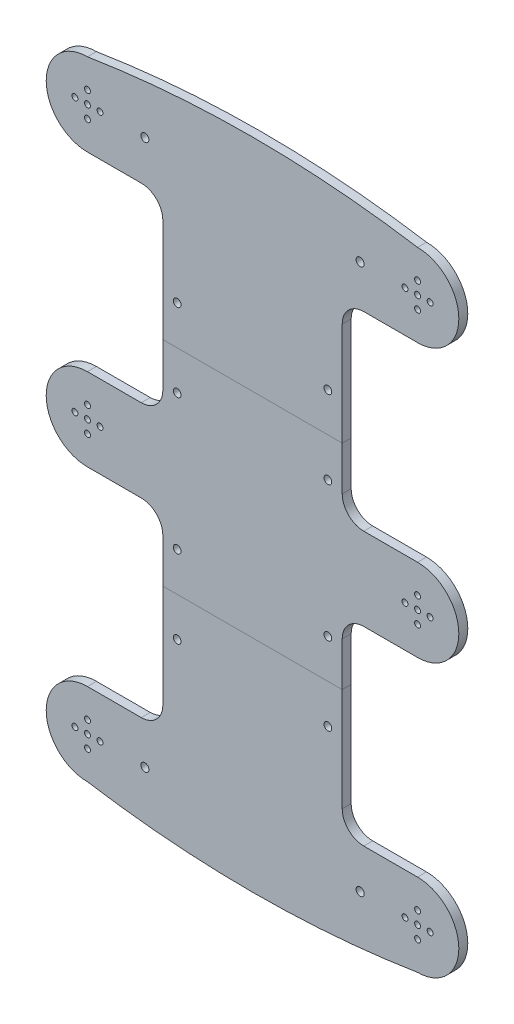
SolidWorks part; units mm, degrees
ref_plane "Płaszczyzna przednia" through (0, 0, 0) normal (0, 0, 1) x (1, 0, 0)
ref_plane "Płaszczyzna górna" through (0, 0, 0) normal (0, 1, 0) x (1, 0, 0)
ref_plane "Płaszczyzna prawa" through (0, 0, 0) normal (1, 0, 0) x (0, 0, -1)
sketch "Szkic1" plane through (0, 0, 0) normal (0, 0, 1) x (1, 0, 0)
  line L0 (-203.4983, 203.4983) -> (200.3017, -200.3017) construction
  line L5 (-225.8431, 0) -> (204.6382, 0) construction
  line L6 (0, 259.0582) -> (0, -261.5805) construction
  line L7 (202.2417, 202.2417) -> (-202.2417, -202.2417) construction
  line L9 (-95, 116) -> (-57, 116) construction
  line L10 (-95, 116) -> (-95, 36) construction
  line L11 (-95, 36) -> (-57, 36) construction
  line L12 (-57, 116) -> (-57, 36) construction
  line L28 (-50, -116.999) -> (-50, -35.001)
  line L29 (50, -116.999) -> (50, -35.001)
  line L31 (-95, 116) -> (-57, 36) construction
  line L32 (-57, 116) -> (-95, 36) construction
  line L33 (-62, -23.001) -> (-92, -23.001)
  line L38 (-50, 35.001) -> (-50, 116.999)
  line L39 (-62, 23.001) -> (-92, 23.001)
  line L42 (50, 35.001) -> (50, 116.999)
  line L43 (-112.0619, 76) -> (134.9818, 76) construction
  line L44 (-112.0619, -76) -> (134.9818, -76) construction
  line L46 (-62, 128.999) -> (-92, 128.999)
  line L48 (-62, -128.999) -> (-92, -128.999)
  line L53 (62, -128.999) -> (92, -128.999)
  line L54 (62, 23.001) -> (92, 23.001)
  line L55 (62, -23.001) -> (92, -23.001)
  line L57 (62, 128.999) -> (92, 128.999)
  circle A0 centre (-92, 7.001) radius 1.65
  circle A4 centre (-92, 0) radius 7.001 construction
  circle A5 centre (-84.999, 0) radius 1.65
  circle A6 centre (-92, -7.001) radius 1.65
  circle A7 centre (-99.001, 0) radius 1.65
  arc A19 (-92, 23.001) -> (-92, -23.001) centre (-92, 0) ccw
  arc A20 (-62, -23.001) -> (-50, -35.001) centre (-62, -35.001) cw
  arc A21 (-62, 23.001) -> (-50, 35.001) centre (-62, 35.001) ccw
  circle A29 centre (-92, 159.001) radius 1.65
  circle A30 centre (-99.001, 152) radius 1.65
  circle A31 centre (-92, 144.999) radius 1.65
  circle A32 centre (-84.999, 152) radius 1.65
  circle A33 centre (-92, -144.999) radius 1.65
  arc A34 (-92, 128.999) -> (-92, 175.001) centre (-92, 152) cw
  arc A35 (-62, 128.999) -> (-50, 116.999) centre (-62, 116.999) cw
  circle A36 centre (-99.001, -152) radius 1.65
  circle A37 centre (-92, -159.001) radius 1.65
  circle A38 centre (-84.999, -152) radius 1.65
  arc A39 (-62, -128.999) -> (-50, -116.999) centre (-62, -116.999) ccw
  arc A40 (-92, -175.001) -> (-92, -128.999) centre (-92, -152) cw
  arc A41 (62, -128.999) -> (50, -116.999) centre (62, -116.999) cw
  arc A42 (92, -175.001) -> (92, -128.999) centre (92, -152) ccw
  circle A43 centre (84.999, -152) radius 1.65
  circle A44 centre (92, -159.001) radius 1.65
  circle A45 centre (99.001, -152) radius 1.65
  circle A46 centre (92, -144.999) radius 1.65
  arc A47 (62, -23.001) -> (50, -35.001) centre (62, -35.001) ccw
  arc A48 (62, 23.001) -> (50, 35.001) centre (62, 35.001) cw
  circle A49 centre (92, 0) radius 7.001 construction
  arc A50 (92, 23.001) -> (92, -23.001) centre (92, 0) cw
  circle A51 centre (99.001, 0) radius 1.65
  circle A52 centre (92, -7.001) radius 1.65
  circle A53 centre (84.999, 0) radius 1.65
  circle A54 centre (92, 7.001) radius 1.65
  arc A55 (62, 128.999) -> (50, 116.999) centre (62, 116.999) ccw
  arc A56 (92, 128.999) -> (92, 175.001) centre (92, 152) ccw
  circle A57 centre (84.999, 152) radius 1.65
  circle A58 centre (92, 144.999) radius 1.65
  circle A59 centre (99.001, 152) radius 1.65
  circle A60 centre (92, 159.001) radius 1.65
  arc A61 (-92, 175.001) -> (92, 175.001) centre (0, -400.8456) cw
  arc A62 (-92, -175.001) -> (92, -175.001) centre (0, 400.8456) ccw
  circle A63 centre (-92, 0) radius 1.65
  circle A64 centre (-92, -152) radius 1.65
  circle A65 centre (-92, 152) radius 1.65
  circle A66 centre (92, -152) radius 1.65
  circle A67 centre (92, 152) radius 1.65
  circle A68 centre (92, 0) radius 1.65
  point P0 (0, 0)
  point P30 (0, 175.001)
  point P32 (50, 0)
  point P33 (-50, 0)
  point P44 (-92, 0)
  point P55 (-76, 76)
  point P60 (-50, -23.001)
  point P63 (-50, 23.001)
  point P65 (-57, 76)
  point P135 (92, 0)
  dimension "D5" = 3.3
  dimension "D7" = 4
  dimension "D11" = 3.3
  dimension "D9" = 12
  dimension "D10" = 583.1495
  dimension "D1" = 45
  dimension "D2" = 45
  dimension "D3" = 38
  dimension "D4" = 80
  dimension "D6" = 7.001
  dimension "D8" = 100
  dimension "D14" = 7
  dimension "D17" = 92
  dimension "D18" = 16
extrude "Dodanie-wyciągnięcie1" add sketch "Szkic1" along normal blind 5
sketch "Szkic2" plane through (-50, 0, 0) normal (-1, 0, 0) x (0, 0, 1)
  line L0 (-4.6021, 76) -> (9.4932, 76) construction
  line L1 (-7.082, -76) -> (18.5034, -76) construction
sketch "Szkic3" plane through (0, 0, 5) normal (0, 0, 1) x (1, 0, 0)
  line L0 (-62, -126.5053) -> (-62, -187.1784) construction
  line L1 (-118.7246, -152) -> (-39.1989, -152) construction
  line L2 (0, -202.5372) -> (0, 222.1546) construction
  line L3 (-132.7754, 0) -> (185.2586, 0) construction
  arc A0 (-92, -128.999) -> (-92, -175.001) centre (-92, -152) ccw construction
  circle A1 centre (-60, -152) radius 2.25
  circle A2 centre (60, -152) radius 2.25
  circle A3 centre (60, 152) radius 2.25
  circle A4 centre (-60, 152) radius 2.25
  point P9 (-115.001, -152)
  dimension "D1" = 4.5
  dimension "D2" = 2
extrude "Wytnij-wyciągnięcie1" cut sketch "Szkic3" against normal through all
sketch "Szkic4" plane through (0, 0, 5) normal (0, 0, 1) x (1, 0, 0)
  line L0 (-74.8423, -59.499) -> (86.4683, -59.499) construction
  line L1 (-74.8423, 59.499) -> (86.4683, 59.499) construction
  line L2 (-62, -128.999) -> (-92, -128.999) construction
  line L3 (-92, 128.999) -> (-62, 128.999) construction
  line L4 (-50, -35.001) -> (-50, -116.999) construction
  line L5 (0, -214.1443) -> (0, 223.9606) construction
  line L6 (-128.0062, 0) -> (132.2343, 0) construction
  circle A0 centre (-42, -37.749) radius 2.15
  circle A1 centre (-42, -81.249) radius 2.15
  circle A2 centre (42, -81.249) radius 2.15
  circle A3 centre (42, -37.749) radius 2.15
  circle A4 centre (42, 37.749) radius 2.15
  circle A5 centre (42, 81.249) radius 2.15
  circle A6 centre (-42, 81.249) radius 2.15
  circle A7 centre (-42, 37.749) radius 2.15
  dimension "D3" = 4.3
  dimension "D5" = 8
  dimension "D1" = 69.5
  dimension "D2" = 69.5
  dimension "D4" = 21.75
extrude "Wytnij-wyciągnięcie2" cut sketch "Szkic4" against normal through all
sketch "Szkic5" plane through (0, 0, 5) normal (0, 0, 1) x (1, 0, 0)
  line L0 (-70.967, -59.501) -> (115.5332, -59.501)
  line L1 (-70.967, 59.501) -> (98.5787, 59.501)
  line L2 (-62, 23.001) -> (-92, 23.001) construction
  line L3 (-92, -23.001) -> (-62, -23.001) construction
  dimension "D1" = 36.5
  dimension "D2" = 36.5
split "Podziel1" trim tools "Szkic5" bodies to split 103 resulting bodies 104 105 106
